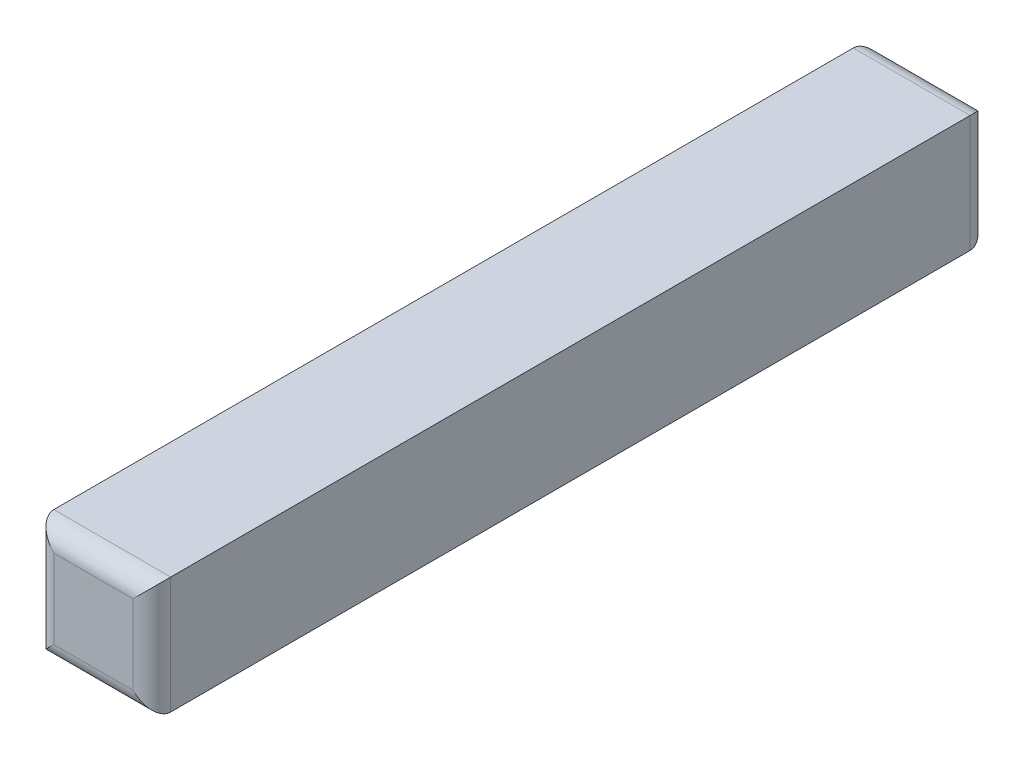
SolidWorks part; units mm, degrees
ref_plane "Plan de face" through (0, 0, 0) normal (0, 0, 1) x (1, 0, 0)
ref_plane "Plan de dessus" through (0, 0, 0) normal (0, 1, 0) x (1, 0, 0)
ref_plane "Plan de droite" through (0, 0, 0) normal (1, 0, 0) x (0, 0, -1)
sketch "Esquisse1" plane through (0, 0, 0) normal (0, 0, 1) x (1, 0, 0)
  line L1 (0, 0) -> (0.62, 0)
  line L2 (0, 0) -> (0, -0.62)
  line L3 (0, -0.62) -> (0.62, -0.62)
  line L4 (0.62, 0) -> (0.62, -0.62)
  dimension "D1" = 0.62
  dimension "D2" = 0.62
extrude "Boss.-Extru.1" add sketch "Esquisse1" along normal blind 4.44
fillet "Congé2" radius 0.1 8 edges at (0.31, 0, 4.44) (0.62, -0.31, 4.44) (0.31, -0.62, 4.44) (0, -0.31, 4.44) (0.31, -0.62, 0) (0.62, -0.31, 0) (0.31, 0, 0) (0, -0.31, 0)
